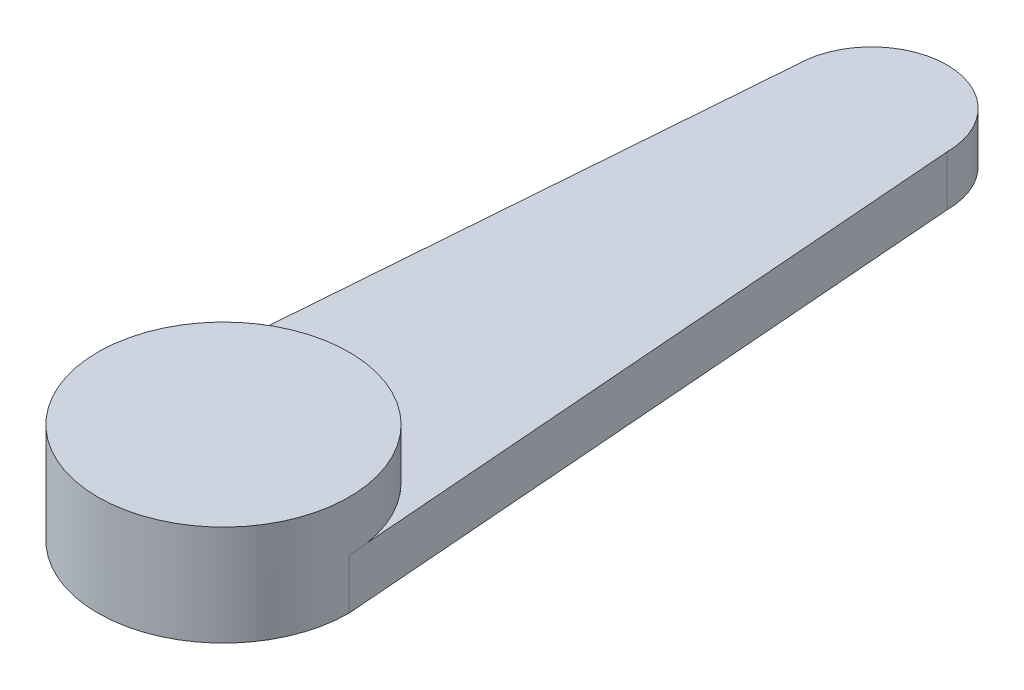
SolidWorks part; units mm, degrees
ref_plane "Front Plane" through (0, 0, 0) normal (0, 0, 1) x (1, 0, 0)
ref_plane "Top Plane" through (0, 0, 0) normal (0, 1, 0) x (1, 0, 0)
ref_plane "Right Plane" through (0, 0, 0) normal (1, 0, 0) x (0, 0, -1)
sketch "Sketch1" plane through (0, 0, 0) normal (0, 1, 0) x (1, 0, 0)
  line L0 (2.3813, 20.4788) -> (3.9688, 0)
  line L1 (-2.3813, 20.4788) -> (-3.9688, 0)
  circle A0 centre (0, 0) radius 3.9688
  circle A1 centre (0, 20.4788) radius 2.3813
  point P9 (0, 0)
  dimension "D1" = 20.4788
  dimension "D2" = 4.7625
  dimension "D3" = 7.9375
extrude "Boss-Extrude1" add sketch "Sketch1" along normal blind 1.5875 contours L0 A0 L1 | A1 L1 A0 L0 | A1
sketch "Sketch2" plane through (0, 1.5875, 0) normal (0, 1, 0) x (1, 0, 0)
  circle A0 centre (0, 0) radius 3.9688
  arc A1 (-3.9688, 0) -> (3.9688, 0) centre (0, 0) ccw construction
extrude "Boss-Extrude2" add sketch "Sketch2" along normal blind 1.5875
